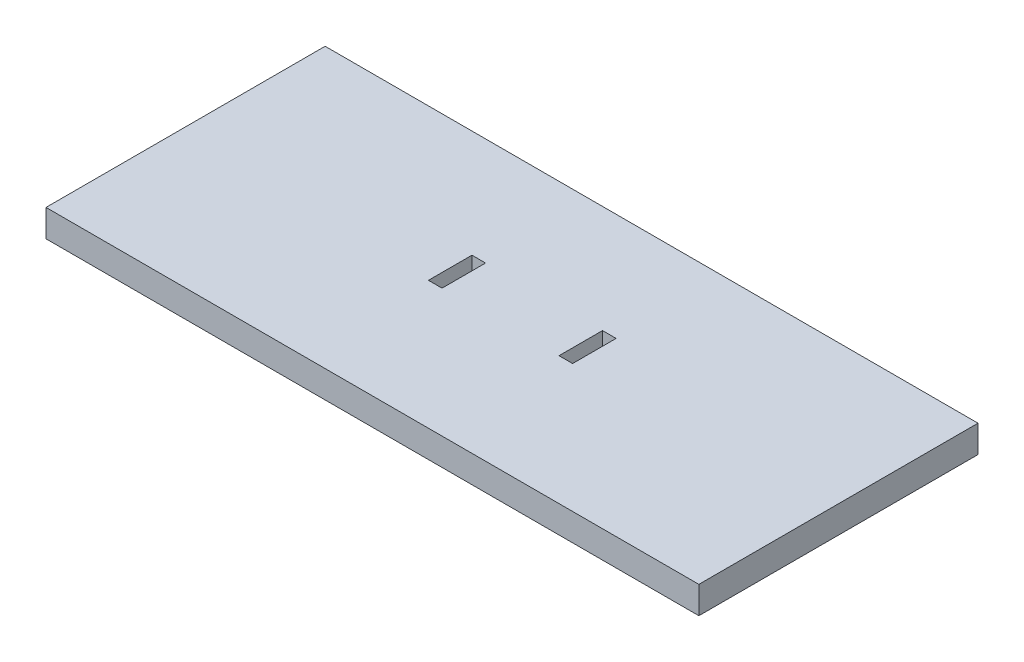
SolidWorks part; units mm, degrees
ref_plane "Front Plane" through (0, 0, 0) normal (0, 0, 1) x (1, 0, 0)
ref_plane "Top Plane" through (0, 0, 0) normal (0, 1, 0) x (1, 0, 0)
ref_plane "Right Plane" through (0, 0, 0) normal (1, 0, 0) x (0, 0, -1)
sketch "Sketch1" plane through (0, 0, 0) normal (0, 1, 0) x (1, 0, 0)
  line L0 (0, 13.6298) -> (0, -14.4512) construction
  line L1 (-60, 25.6535) -> (60, 25.6535)
  line L2 (-60, 25.6535) -> (-60, -25.6535)
  line L3 (-60, -25.6535) -> (60, -25.6535)
  line L4 (60, 25.6535) -> (60, -25.6535)
  line L5 (-60, 25.6535) -> (60, -25.6535) construction
  line L6 (-60, -25.6535) -> (60, 25.6535) construction
  line L7 (-13.25, 5.8883) -> (-10.75, 5.8883)
  line L8 (-13.25, 5.8883) -> (-13.25, -2.1117)
  line L9 (-13.25, -2.1117) -> (-10.75, -2.1117)
  line L10 (-10.75, 5.8883) -> (-10.75, -2.1117)
  line L11 (-13.25, 5.8883) -> (-10.75, -2.1117) construction
  line L12 (-13.25, -2.1117) -> (-10.75, 5.8883) construction
  line L13 (13.25, -2.1117) -> (10.75, -2.1117)
  line L14 (13.25, 5.8883) -> (13.25, -2.1117)
  line L15 (13.25, -2.1117) -> (10.75, 5.8883) construction
  line L16 (13.25, 5.8883) -> (10.75, -2.1117) construction
  line L17 (13.25, 5.8883) -> (10.75, 5.8883)
  line L18 (10.75, 5.8883) -> (10.75, -2.1117)
  point P0 (0, 0)
  point P6 (-12, 1.8883)
  dimension "D1" = 120
  dimension "D2" = 51.307
  dimension "D3" = 2.5
  dimension "D4" = 8
  dimension "D5" = 10.75
extrude "Boss-Extrude1" add sketch "Sketch1" along normal blind 5
